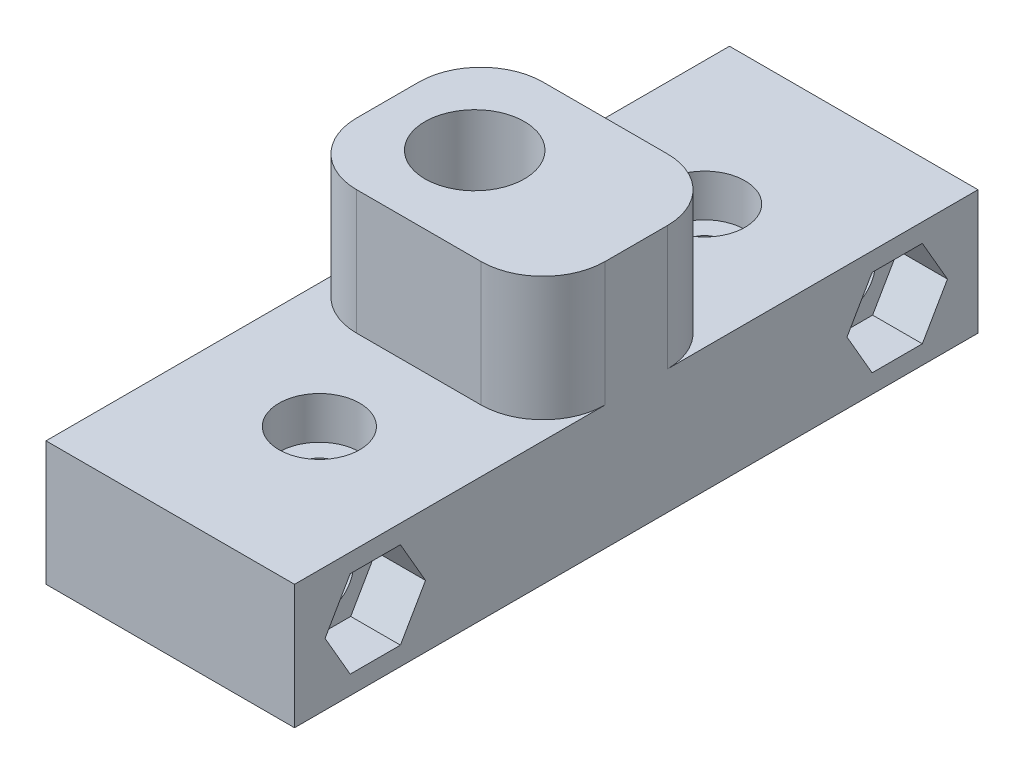
SolidWorks part; units mm, degrees
material "ABS"
ref_plane "Front Plane" through (0, 0, 0) normal (0, 0, 1) x (1, 0, 0)
ref_plane "Top Plane" through (0, 0, 0) normal (0, 1, 0) x (1, 0, 0)
ref_plane "Right Plane" through (0, 0, 0) normal (1, 0, 0) x (0, 0, -1)
sketch "Sketch1" plane through (0, 0, 0) normal (0, 1, 0) x (1, 0, 0)
  line L1 (-10, -27.5) -> (10, -27.5)
  line L2 (-10, -27.5) -> (-10, 27.5)
  line L3 (-10, 27.5) -> (10, 27.5)
  line L4 (10, -27.5) -> (10, 27.5)
  line L5 (-10, -27.5) -> (10, 27.5) construction
  line L6 (-10, 27.5) -> (10, -27.5) construction
  point P1 (0, 0)
  dimension "D1" = 20
  dimension "D2" = 55
extrude "Boss-Extrude1" add sketch "Sketch1" along normal blind 20
sketch "Sketch2" plane through (0, 20, 0) normal (0, 1, 0) x (1, 0, 0)
  line L0 (-10, 27.5) -> (-10, -27.5) construction
  circle A0 centre (-3, 0) radius 4
  dimension "D2" = 8
  dimension "D1" = 7
extrude "Cut-Extrude1" cut sketch "Sketch2" against normal blind 10
sketch "Sketch3" plane through (0, 20, 0) normal (0, 1, 0) x (1, 0, 0)
  line L0 (10, -27.5) -> (10, 27.5) construction
  line L1 (-10, -27.5) -> (10, -27.5)
  line L2 (-10, -27.5) -> (-10, -7.5)
  line L3 (-10, -7.5) -> (10, -7.5)
  line L4 (10, -27.5) -> (10, -7.5)
  line L6 (-10, 27.5) -> (10, 27.5)
  line L7 (-10, 27.5) -> (-10, 7.5)
  line L8 (-10, 7.5) -> (10, 7.5)
  line L9 (10, 27.5) -> (10, 7.5)
  dimension "D1" = 20
  dimension "D2" = 20
extrude "Cut-Extrude2" cut sketch "Sketch3" against normal blind 10
sketch "Sketch6" plane through (0, 0, 0) normal (0, -1, 0) x (1, 0, 0)
  line L0 (10, 27.5) -> (10, -27.5) construction
  line L1 (-10, 27.5) -> (10, 27.5)
  line L2 (-10, 27.5) -> (-10, -27.5)
  line L3 (-10, -27.5) -> (10, -27.5)
  line L4 (10, 27.5) -> (10, -27.5)
  line L5 (-10, 27.5) -> (10, -27.5) construction
  line L6 (-10, -27.5) -> (10, 27.5) construction
  point P0 (0, 0)
  dimension "D1" = 55
extrude "Boss-Extrude2" [suppressed] add sketch "Sketch6" along normal blind 10
hole_wizard "CBORE for M3 Hex Socket Head Cap Screw1" positions "Sketch4" profile "Sketch5" counterbore size "M3" standard "ISO" end condition through all
sketch "Sketch4" plane through (0, 10, 0) normal (0, 1, 0) x (1, 0, 0)
  line L1 (-10, -27.5) -> (10, -27.5) construction
  line L2 (10, 27.5) -> (-10, 27.5) construction
  point P0 (0, -15.5)
  point P2 (0, 15.5)
  dimension "D1" = 12
  dimension "D2" = 12
sketch "Sketch5" plane through (0, 10, 15.5) normal (1, 0, 0) x (0, 0, 1)
  line L0 (0, 0) -> (0, 10)
  line L1 (0, 10) -> (1.7, 10)
  line L3 (1.7, 10) -> (1.7, 3.4)
  line L4 (1.7, 3.4) -> (3.25, 3.4)
  line L5 (3.25, 3.4) -> (3.25, 0)
  line L7 (3.25, 0) -> (0, 0)
  line L11 (0, -6.35) -> (0, 107.95) construction
  dimension "Thru Hole Dia." = 3.4
  dimension "Thru Hole Depth" = 10
  dimension "C'Bore Dia." = 6.5
  dimension "C'Bore Depth" = 3.4
fillet "Fillet2" radius 5 4 edges at (-10, 15, -7.5) (-10, 15, 7.5) (10, 15, -7.5) (10, 15, 7.5)
sketch "Sketch7" [suppressed] plane through (10, 0, 0) normal (1, 0, 0) x (0, 0, -1)
  line L0 (27.5, -10) -> (-27.5, -10) construction
  line L1 (-27.5, -10) -> (-27.5, 0) construction
  circle A0 centre (-21, -5) radius 2.25
  circle A1 centre (21, -5) radius 2.25
  dimension "D1" = 4.5
  dimension "D4" = 4.5
  dimension "D2" = 5
  dimension "D3" = 6.5
  dimension "D5" = 42
extrude "Cut-Extrude3" [suppressed] cut sketch "Sketch7" against normal through all
sketch "Sketch8" [suppressed] plane through (10, 0, 0) normal (1, 0, 0) x (0, 0, -1)
  line L1 (-16.7276, -5) -> (-18.8638, -1.3)
  line L2 (-18.8638, -1.3) -> (-23.1362, -1.3)
  line L3 (-23.1362, -1.3) -> (-25.2724, -5)
  line L4 (-25.2724, -5) -> (-23.1362, -8.7)
  line L5 (-23.1362, -8.7) -> (-18.8638, -8.7)
  line L6 (-18.8638, -8.7) -> (-16.7276, -5)
  line L7 (16.7276, -5) -> (18.8638, -8.7)
  line L8 (18.8638, -8.7) -> (23.1362, -8.7)
  line L9 (23.1362, -8.7) -> (25.2724, -5)
  line L10 (25.2724, -5) -> (23.1362, -1.3)
  line L11 (23.1362, -1.3) -> (18.8638, -1.3)
  line L12 (18.8638, -1.3) -> (16.7276, -5)
  circle A0 centre (-21, -5) radius 3.7 construction
  circle A1 centre (21, -5) radius 3.7 construction
  dimension "D1" = 7.4
  dimension "D2" = 7.4
extrude "Cut-Extrude4" [suppressed] cut sketch "Sketch8" against normal blind 4
fillet "Fillet3" [suppressed] radius 5
fillet "Fillet4" [suppressed] radius 5
sketch "Sketch9" plane through (-10, 0, 0) normal (-1, 0, 0) x (0, 0, 1)
  line L0 (-27.5, 0) -> (27.5, 0) construction
  line L1 (-27.5, 10) -> (-27.5, 0) construction
  circle A0 centre (-21, 5) radius 2.25
  circle A1 centre (21, 5) radius 2.25
  dimension "D2" = 4.5
  dimension "D5" = 4.5
  dimension "D1" = 5
  dimension "D3" = 6.5
  dimension "D4" = 42
extrude "Cut-Extrude5" cut sketch "Sketch9" against normal through all
sketch "Sketch10" plane through (10, 0, 0) normal (1, 0, 0) x (0, 0, -1)
  line L1 (-16.9585, 5) -> (-18.9793, 8.5)
  line L2 (-18.9793, 8.5) -> (-23.0207, 8.5)
  line L3 (-23.0207, 8.5) -> (-25.0415, 5)
  line L4 (-25.0415, 5) -> (-23.0207, 1.5)
  line L5 (-23.0207, 1.5) -> (-18.9793, 1.5)
  line L6 (-18.9793, 1.5) -> (-16.9585, 5)
  line L7 (16.9585, 5) -> (18.9793, 1.5)
  line L8 (18.9793, 1.5) -> (23.0207, 1.5)
  line L9 (23.0207, 1.5) -> (25.0415, 5)
  line L10 (25.0415, 5) -> (23.0207, 8.5)
  line L11 (23.0207, 8.5) -> (18.9793, 8.5)
  line L12 (18.9793, 8.5) -> (16.9585, 5)
  circle A0 centre (-21, 5) radius 3.5 construction
  circle A1 centre (21, 5) radius 3.5 construction
  dimension "D1" = 7
  dimension "D2" = 7
extrude "Cut-Extrude6" cut sketch "Sketch10" against normal blind 4
